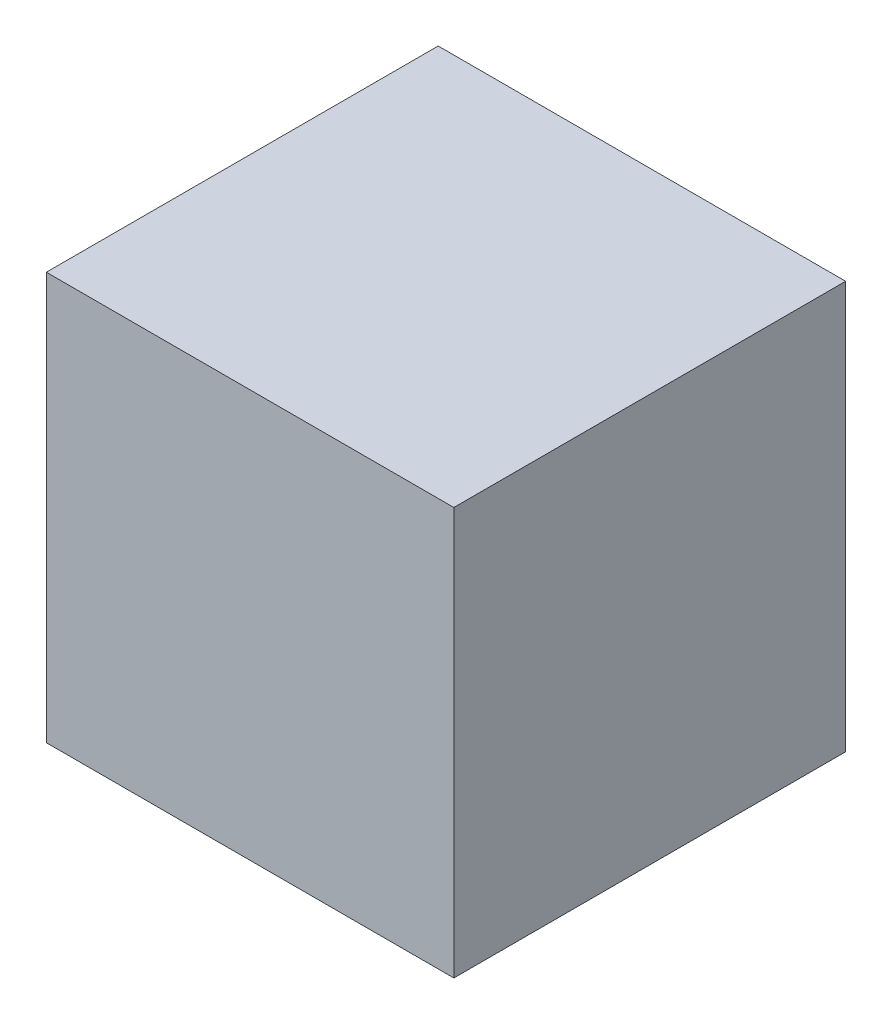
SolidWorks part; units mm, degrees
ref_plane "Front Plane" through (0, 0, 0) normal (0, 0, 1) x (1, 0, 0)
ref_plane "Top Plane" through (0, 0, 0) normal (0, 1, 0) x (1, 0, 0)
ref_plane "Right Plane" through (0, 0, 0) normal (1, 0, 0) x (0, 0, -1)
sketch "Sketch1" plane through (0, 0, 0) normal (0, 0, 1) x (1, 0, 0)
  line L1 (-3.302, -3.302) -> (3.302, -3.302)
  line L2 (-3.302, -3.302) -> (-3.302, 3.302)
  line L3 (-3.302, 3.302) -> (3.302, 3.302)
  line L4 (3.302, -3.302) -> (3.302, 3.302)
  line L5 (-3.302, -3.302) -> (3.302, 3.302) construction
  line L6 (-3.302, 3.302) -> (3.302, -3.302) construction
  point P0 (0, 0)
  dimension "D1" = 6.604
extrude "Boss-Extrude1" add sketch "Sketch1" along normal blind 6.35
sketch "Sketch2" plane through (0, 0, 0) normal (0, 0, -1) x (-1, 0, 0)
  circle A0 centre (0, 0) radius 0.8255
  dimension "D1" = 1.651
extrude "Boss-Extrude2" add sketch "Sketch2" along normal blind 1.27
equation "\"D1@Sketch2\" = \"D1@Sketch1\"/4"
